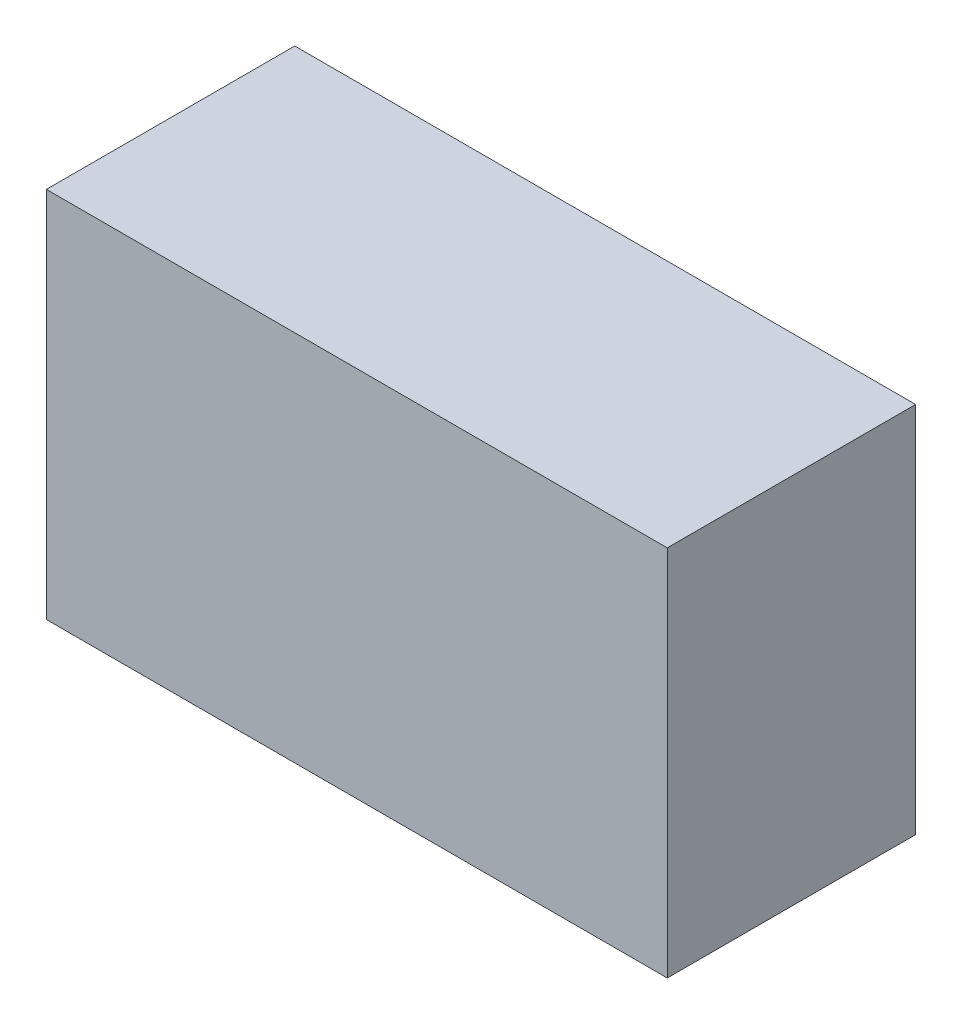
SolidWorks part; units mm, degrees
ref_plane "前视基准面" through (0, 0, 0) normal (0, 0, 1) x (1, 0, 0)
ref_plane "上视基准面" through (0, 0, 0) normal (0, 1, 0) x (1, 0, 0)
ref_plane "右视基准面" through (0, 0, 0) normal (1, 0, 0) x (0, 0, -1)
sketch "草图1" plane through (0, 0, 0) normal (0, 0, 1) x (1, 0, 0)
  line L1 (-4.1875, 11.1562) -> (20.8125, 11.1562)
  line L2 (-4.1875, 11.1562) -> (-4.1875, -3.8438)
  line L3 (-4.1875, -3.8438) -> (20.8125, -3.8438)
  line L4 (20.8125, 11.1562) -> (20.8125, -3.8438)
  dimension "D1" = 15
  dimension "D2" = 25
extrude "凸台-拉伸1" add sketch "草图1" along normal blind 10
